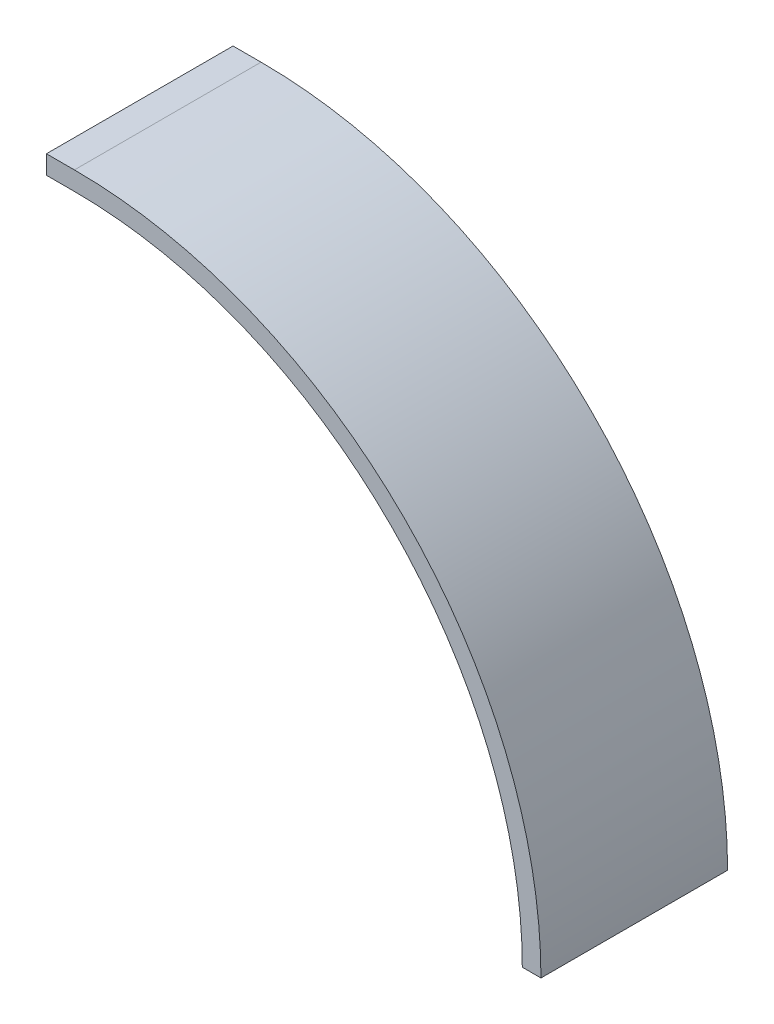
SolidWorks part; units mm, degrees
ref_plane "Front Plane" through (0, 0, 0) normal (0, 0, 1) x (1, 0, 0)
ref_plane "Top Plane" through (0, 0, 0) normal (0, 1, 0) x (1, 0, 0)
ref_plane "Right Plane" through (0, 0, 0) normal (1, 0, 0) x (0, 0, -1)
sketch "Sketch1" plane through (0, 0, 0) normal (0, 0, 1) x (1, 0, 0)
  line L0 (-45.486, 0.9595) -> (-45.486, -1.0405)
  line L1 (2.514, -49.0405) -> (4.514, -49.0405)
  line L2 (-45.7386, 0) -> (28.8434, 0) construction
  arc A0 (-45.486, -1.0405) -> (2.514, -49.0405) centre (-45.486, -49.0405) cw
  arc A1 (-45.486, 0.9595) -> (4.514, -49.0405) centre (-45.486, -49.0405) cw
  dimension "D1" = 2
  dimension "D2" = 48
extrude "Boss-Extrude1" add sketch "Sketch1" along normal blind 20
sketch "Sketch2" plane through (-45.486, 0, 0) normal (-1, 0, 0) x (0, 0, 1)
  line L0 (20, -1.0405) -> (0, -1.0405) construction
  line L1 (0, 0.9595) -> (20, 0.9595)
  line L2 (0, 0.9595) -> (0, -1.0405)
  line L3 (0, -1.0405) -> (20, -1.0405)
  line L4 (20, 0.9595) -> (20, -1.0405)
  line L5 (20, -49.0405) -> (20, -1.0405) construction
extrude "Boss-Extrude2" add sketch "Sketch2" along normal blind 3
sketch "Sketch3" plane through (0, -49.0405, 0) normal (0, -1, 0) x (1, 0, 0)
  line L1 (2.514, 0) -> (4.514, 0)
  line L2 (2.514, 0) -> (2.514, 20)
  line L3 (2.514, 20) -> (4.514, 20)
  line L4 (4.514, 0) -> (4.514, 20)
